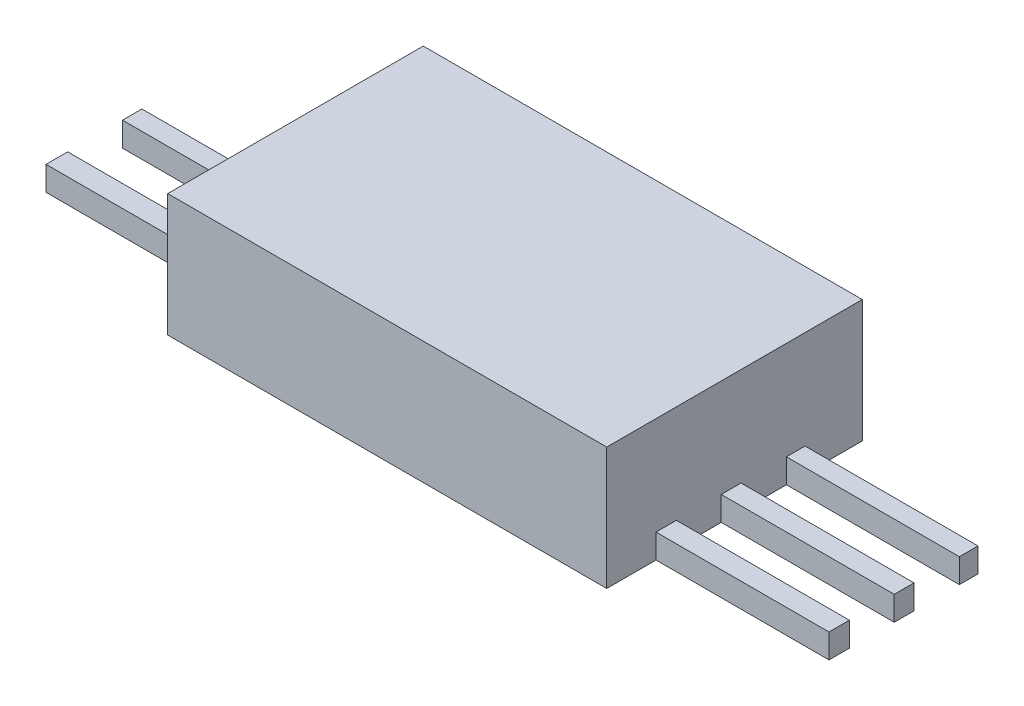
SolidWorks part; units mm, degrees
ref_plane "Front Plane" through (0, 0, 0) normal (0, 0, 1) x (1, 0, 0)
ref_plane "Top Plane" through (0, 0, 0) normal (0, 1, 0) x (1, 0, 0)
ref_plane "Right Plane" through (0, 0, 0) normal (1, 0, 0) x (0, 0, -1)
sketch "Sketch1" plane through (0, 0, 0) normal (0, 1, 0) x (1, 0, 0)
  line L1 (0, 0) -> (67, 0)
  line L2 (0, 0) -> (0, 39)
  line L3 (0, 39) -> (67, 39)
  line L4 (67, 0) -> (67, 39)
  dimension "D1" = 67
  dimension "D2" = 39
extrude "Boss-Extrude1" add sketch "Sketch1" along normal blind 18.7
sketch "Sketch2" plane through (0, 0, 0) normal (0, -1, 0) x (1, 0, 0)
  line L0 (0, -39) -> (0, 0) construction
  line L1 (0, -9.5752) -> (-28.1539, -9.5752)
  line L2 (0, -9.5752) -> (0, -12.8835)
  line L3 (0, -12.8835) -> (-28.1539, -12.8835)
  line L4 (-28.1539, -9.5752) -> (-28.1539, -12.8835)
  line L5 (67, 0) -> (67, -39) construction
  line L6 (0, -21.2544) -> (-28.1539, -21.2544)
  line L7 (0, -21.2544) -> (0, -24.2118)
  line L8 (0, -24.2118) -> (-28.1539, -24.2118)
  line L9 (-28.1539, -21.2544) -> (-28.1539, -24.2118)
  line L10 (67, -7.5201) -> (93.3995, -7.5201)
  line L11 (67, -7.5201) -> (67, -10.6279)
  line L12 (67, -10.6279) -> (93.3995, -10.6279)
  line L13 (93.3995, -7.5201) -> (93.3995, -10.6279)
  line L27 (67, -17.4749) -> (93.3995, -17.4749)
  line L28 (67, -17.4749) -> (67, -20.4938)
  line L29 (67, -20.4938) -> (93.3995, -20.4938)
  line L30 (93.3995, -17.4749) -> (93.3995, -20.4938)
  line L31 (67, -27.4194) -> (93.3995, -27.4194)
  line L32 (67, -27.4194) -> (67, -30.2607)
  line L33 (67, -30.2607) -> (93.3995, -30.2607)
  line L34 (93.3995, -27.4194) -> (93.3995, -30.2607)
extrude "Boss-Extrude2" add sketch "Sketch2" against normal blind 3.7
